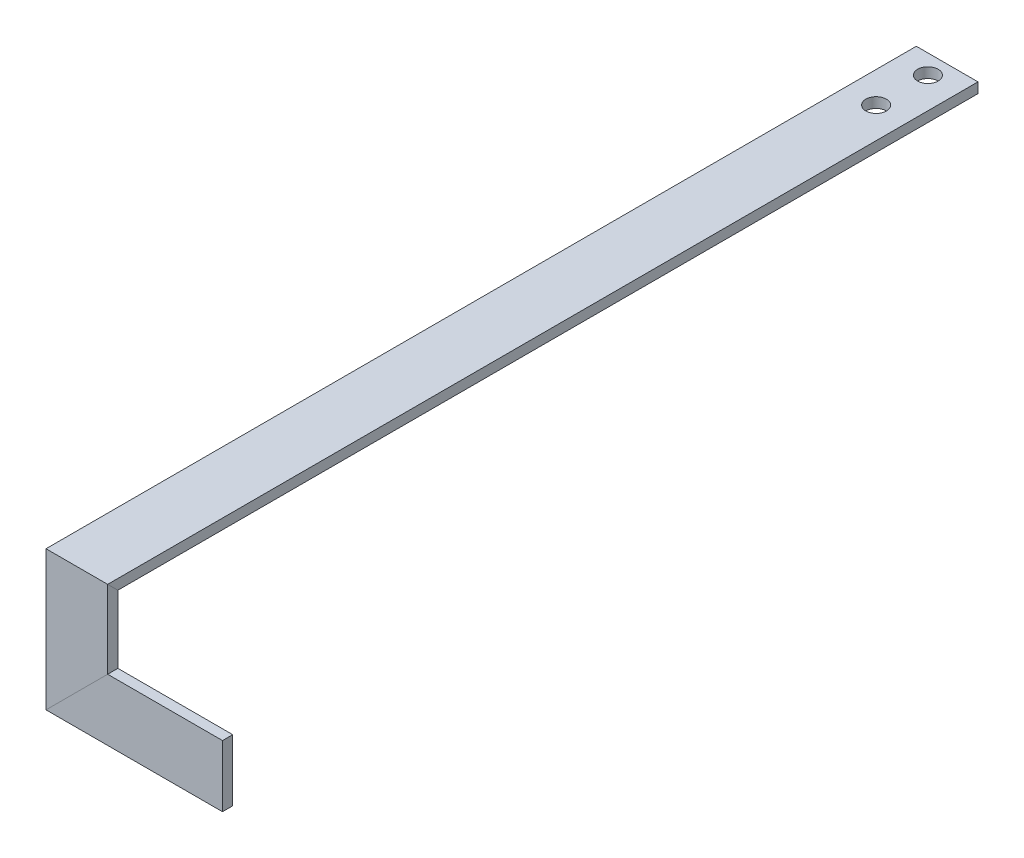
SolidWorks part; units mm, degrees
ref_plane "Alzado" through (0, 0, 0) normal (0, 0, 1) x (1, 0, 0)
ref_plane "Planta" through (0, 0, 0) normal (0, 1, 0) x (1, 0, 0)
ref_plane "Vista lateral" through (0, 0, 0) normal (1, 0, 0) x (0, 0, -1)
sketch "Croquis1" plane through (0, 0, 0) normal (0, 0, 1) x (1, 0, 0)
  line L1 (-19.05, 3.155) -> (19.05, 3.155)
  line L2 (-19.05, 3.155) -> (-19.05, -3.155)
  line L3 (-19.05, -3.155) -> (19.05, -3.155)
  line L4 (19.05, 3.155) -> (19.05, -3.155)
  line L5 (-19.05, 3.155) -> (19.05, -3.155) construction
  line L6 (-19.05, -3.155) -> (19.05, 3.155) construction
  point P0 (0, 0)
  dimension "D1" = 38.1
  dimension "D2" = 6.31
sketch3d "Croquis3D2"
  line L0 (0, 0, 0) -> (0, 0, 534.55)
  line L1 (0, 0, 534.55) -> (0, -64, 534.55)
  line L2 (0, -64, 534.55) -> (90, -64, 534.55)
  dimension "D1" = 534.55
  dimension "D2" = 64
  dimension "D3" = 90
sweep "Barrer1" add profiles "Croquis1" path "Croquis3D2"
sketch "Croquis2" plane through (0, 3.155, 0) normal (0, 1, 0) x (1, 0, 0)
  circle A0 centre (0, -43.8922) radius 6.35
  circle A1 centre (0, -11.8922) radius 6.35
extrude "Cortar-Extruir1" cut sketch "Croquis2" against normal blind 6.31
